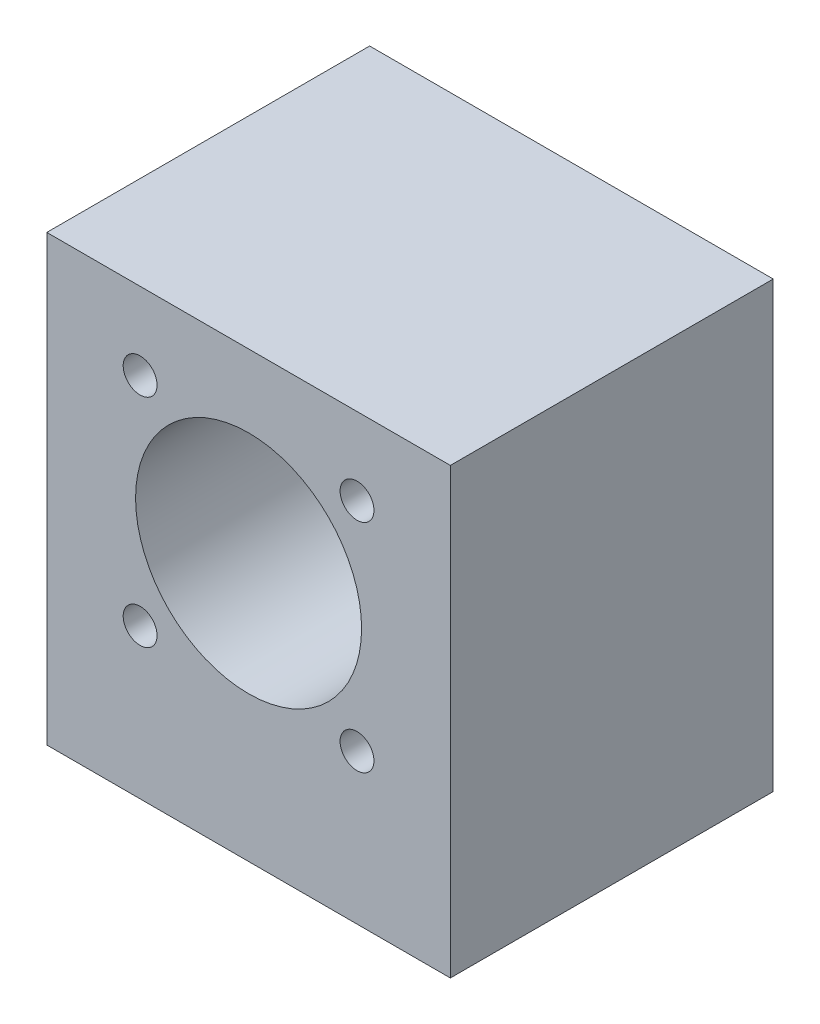
SolidWorks part; units mm, degrees
ref_plane "Front Plane" through (0, 0, 0) normal (0, 0, 1) x (1, 0, 0)
ref_plane "Top Plane" through (0, 0, 0) normal (0, 1, 0) x (1, 0, 0)
ref_plane "Right Plane" through (0, 0, 0) normal (1, 0, 0) x (0, 0, -1)
sketch "Sketch1" plane through (0, 0, 0) normal (0, 0, 1) x (1, 0, 0)
  line L1 (25, -27.5) -> (-25, -27.5)
  line L2 (25, -27.5) -> (25, 27.5)
  line L3 (25, 27.5) -> (-25, 27.5)
  line L4 (-25, -27.5) -> (-25, 27.5)
  line L5 (25, -27.5) -> (-25, 27.5) construction
  line L6 (25, 27.5) -> (-25, -27.5) construction
  point P0 (0, 0)
  dimension "D1" = 50
  dimension "D2" = 55
extrude "Boss-Extrude1" add sketch "Sketch1" against normal blind 40
sketch "Sketch2" plane through (0, 0, 0) normal (0, 0, 1) x (1, 0, 0)
  line L0 (0, 27.5) -> (0, -27.5) construction
  line L1 (25, 27.5) -> (-25, 27.5) construction
  line L2 (-25, -27.5) -> (25, -27.5) construction
  line L3 (-25, 4.5) -> (25, 4.5) construction
  line L4 (-25, 27.5) -> (-25, -27.5) construction
  line L5 (25, -27.5) -> (25, 27.5) construction
  circle A0 centre (0, 4.5) radius 14
  dimension "D1" = 28
  dimension "D2" = 23
extrude "Cut-Extrude1" cut sketch "Sketch2" against normal through all
sketch "Sketch3" plane through (0, 0, 0) normal (0, 0, 1) x (1, 0, 0)
  line L0 (0, 4.5) -> (13.435, 17.935) construction
  line L1 (0, 4.5) -> (19, 4.5) construction
  line L3 (0, 4.5) -> (0, -14.5) construction
  circle A0 centre (0, 4.5) radius 19 construction
  point P3 (-13.435, 17.935)
  point P7 (13.435, -8.935)
  point P8 (-13.435, -8.935)
  dimension "D1" = 38
  dimension "D2" = 45
sketch "Sketch4" plane through (0, -27.5, 0) normal (0, -1, 0) x (1, 0, 0)
  line L0 (0, 0) -> (0, -40) construction
  line L1 (19, 0) -> (-19, 0) construction
  line L2 (-25, -40) -> (25, -40) construction
  line L3 (-25, -20) -> (25, -20) construction
  line L4 (-25, -40) -> (-25, 0) construction
  line L5 (25, -40) -> (25, 0) construction
  point P12 (-10, -10)
  point P13 (10, -10)
  point P14 (10, -30)
  point P15 (-10, -30)
  dimension "D1" = 10
  dimension "D2" = 10
hole_wizard "M5 Tapped Hole1" positions "3DSketch1" profile "Sketch6" tap size "M5" standard "ISO"
sketch3d "3DSketch1"
  point P0 (-10, -27.5, -10)
  point P3 (10, -27.5, -10)
  point P6 (10, -27.5, -30)
  point P9 (-10, -27.5, -30)
sketch "Sketch6" plane through (-10, -27.5, -10) normal (1, 0, 0) x (0, 0, -1)
  line L0 (0, 0) -> (0, 16.2618)
  line L1 (0, 16.2618) -> (2.1, 15)
  line L2 (2.1, 15) -> (2.1, 0)
  line L5 (2.1, 0) -> (0, 0)
  line L10 (0, 16.2618) -> (-2.1, 15) construction
  line L11 (0, -6.35) -> (0, 107.95) construction
  dimension "Tap Drill Dia." = 4.2
  dimension "Tap Drill Depth" = 15
  dimension "Drill Angle" = 118
cosmetic thread "Hole Thread1" parameters "D1"=14.5, "D2"=5
cosmetic thread "Hole Thread2" parameters "D1"=14.5, "D2"=5
cosmetic thread "Hole Thread3" parameters "D1"=14.5, "D2"=5
cosmetic thread "Hole Thread4" parameters "D1"=14.5, "D2"=5
hole_wizard "M5 Tapped Hole3" positions "3DSketch3" profile "Sketch8" tap size "M5" standard "ISO"
sketch3d "3DSketch3"
  point P0 (13.435, 17.935, 0)
  point P3 (13.435, -8.935, 0)
  point P6 (-13.435, -8.935, 0)
  point P9 (-13.435, 17.935, 0)
sketch "Sketch8" plane through (13.435, 17.935, 0) normal (1, 0, 0) x (0, -1, 0)
  line L0 (0, 0) -> (0, 18.6618)
  line L1 (0, 18.6618) -> (2.1, 17.4)
  line L2 (2.1, 17.4) -> (2.1, 0)
  line L5 (2.1, 0) -> (0, 0)
  line L10 (0, 18.6618) -> (-2.1, 17.4) construction
  line L11 (0, -6.35) -> (0, 107.95) construction
  dimension "Tap Drill Dia." = 4.2
  dimension "Tap Drill Depth" = 17.4
  dimension "Drill Angle" = 118
